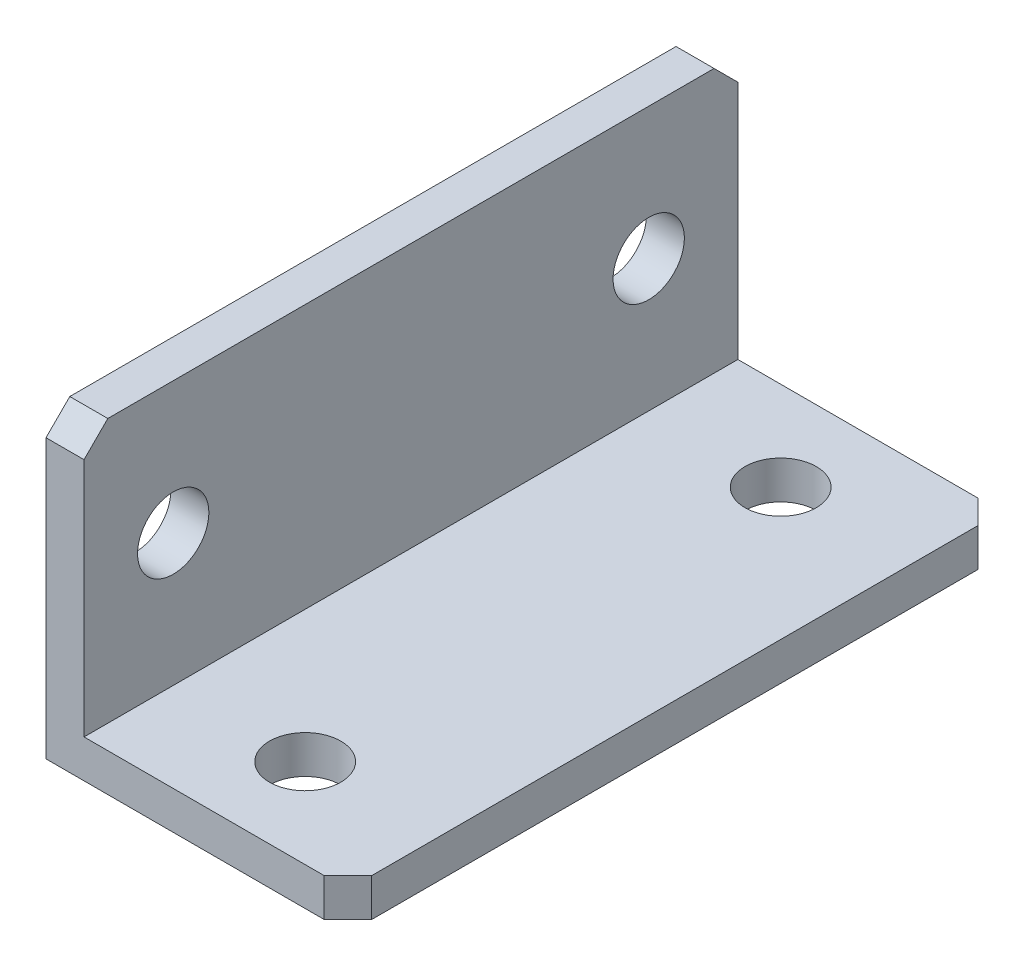
SolidWorks part; units mm, degrees
ref_plane "Plano frontal" through (0, 0, 0) normal (0, 0, 1) x (1, 0, 0)
ref_plane "Plano superior" through (0, 0, 0) normal (0, 1, 0) x (1, 0, 0)
ref_plane "Plano direito" through (0, 0, 0) normal (1, 0, 0) x (0, 0, -1)
sketch "Esboço1" plane through (0, 0, 0) normal (0, 0, 1) x (1, 0, 0)
  line L0 (0, 0) -> (0, 22.2)
  line L1 (0, 22.2) -> (-3.2, 22.2)
  line L2 (-3.2, 22.2) -> (-3.2, -3.2)
  line L3 (-3.2, -3.2) -> (22.2, -3.2)
  line L4 (22.2, -3.2) -> (22.2, 0)
  line L5 (22.2, 0) -> (0, 0)
  dimension "D1" = 3.2
  dimension "D2" = 3.2
  dimension "D3" = 25.4
  dimension "D4" = 25.4
extrude "Ressalto-extrusão1" add sketch "Esboço1" along normal blind 55
chamfer "Chanfro1" distance 2 angle 45 4 edges at (-1.6, 22.2, 0) (-1.6, 22.2, 55) (22.2, -1.6, 0) (22.2, -1.6, 55)
sketch "Esboço2" plane through (0, 0, 0) normal (0, 1, 0) x (1, 0, 0)
  line L0 (11.1, 0) -> (11.1, -55) construction
  line L1 (20.2, 0) -> (0, 0) construction
  line L2 (20.2, -55) -> (0, -55) construction
  line L3 (11.1, -27.5) -> (22.2, -27.5) construction
  line L4 (22.2, -53) -> (22.2, -2) construction
  line L5 (11.1, -27.5) -> (0, -27.5) construction
  line L6 (0, -55) -> (0, 0) construction
  circle A0 centre (11.1, -7.5) radius 3
  circle A1 centre (11.1, -47.5) radius 3
  dimension "D1" = 6
  dimension "D2" = 40
  dimension "D3" = 20
extrude "Corte-extrusão1" cut sketch "Esboço2" against normal through all
sketch "Esboço3" plane through (0, 0, 0) normal (1, 0, 0) x (0, 0, -1)
  line L0 (-55, 11.1) -> (0, 11.1) construction
  line L1 (-55, 0) -> (-55, 20.2) construction
  line L2 (0, 0) -> (0, 20.2) construction
  line L3 (-27.5, 11.1) -> (-27.5, 22.2) construction
  line L4 (-53, 22.2) -> (-2, 22.2) construction
  line L5 (-27.5, 0) -> (-27.5, 11.1) construction
  line L6 (-55, 0) -> (0, 0) construction
  circle A0 centre (-47.5, 11.1) radius 3
  circle A1 centre (-7.5, 11.1) radius 3
  dimension "D1" = 6
  dimension "D2" = 40
  dimension "D3" = 20
extrude "Corte-extrusão2" cut sketch "Esboço3" against normal through all
